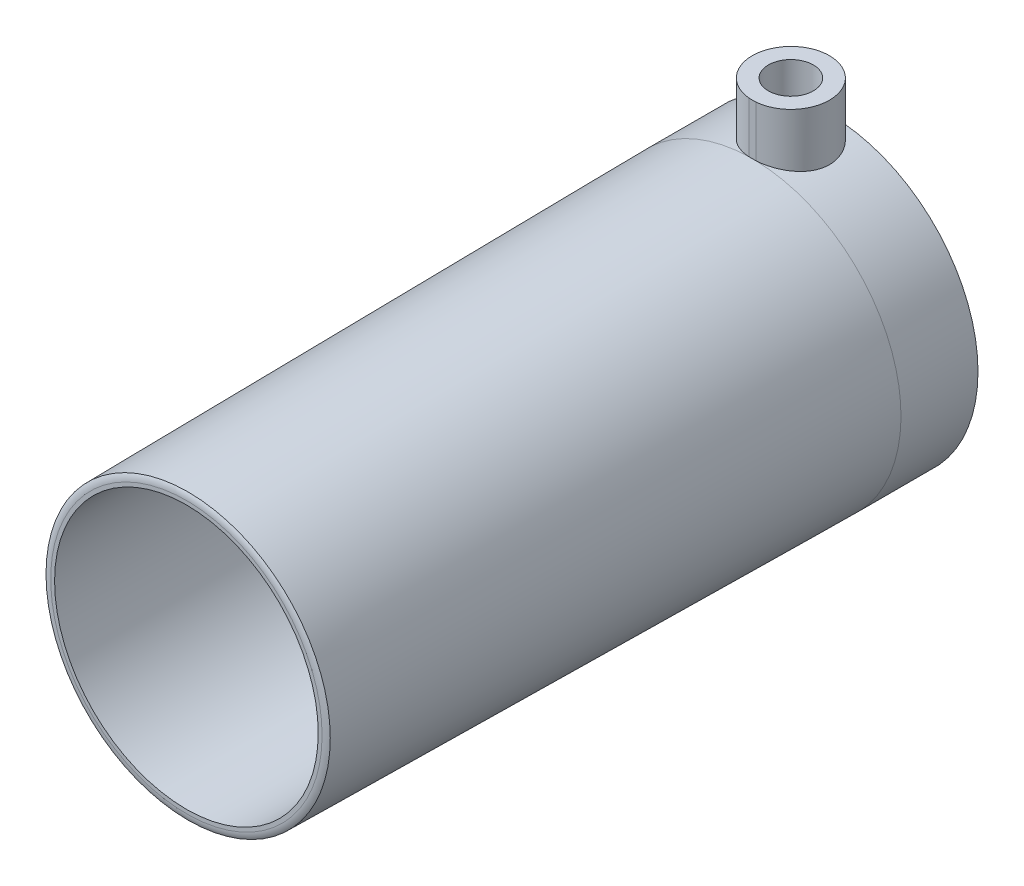
SolidWorks part; units mm, degrees
ref_plane "前视基准面" through (0, 0, 0) normal (0, 0, 1) x (1, 0, 0)
ref_plane "上视基准面" through (0, 0, 0) normal (0, 1, 0) x (1, 0, 0)
ref_plane "右视基准面" through (0, 0, 0) normal (1, 0, 0) x (0, 0, -1)
sketch "草图1" plane through (0, 0, 0) normal (0, 0, 1) x (1, 0, 0)
  circle A0 centre (0, 0) radius 23.1
  circle A1 centre (0, 0) radius 20.5
  dimension "D1" = 46.2
  dimension "D2" = 41
extrude "凸台-拉伸1" add sketch "草图1" along normal blind 100
ref_plane "基准面1" through (0, 21, 0) normal (0, 1, 0) x (1, 0, 0)
sketch "草图2" plane through (0, 21, 0) normal (0, 1, 0) x (1, 0, 0)
  line L0 (0, 0) -> (0, -100) construction
  line L1 (-23.1, -100) -> (23.1, -100) construction
  line L2 (-23.1, 0) -> (23.1, 0) construction
  circle A0 centre (0, -6) radius 6
  dimension "D1" = 12
extrude "凸台-拉伸2" add sketch "草图2" along normal blind 10
sketch "草图3" plane through (0, 31, 0) normal (0, 1, 0) x (1, 0, 0)
  circle A0 centre (0, -6) radius 3.5
  dimension "D1" = 7
extrude "切除-拉伸1" cut sketch "草图3" against normal blind 20
fillet "圆角1" radius 2 1 edges at (23.1, 0, 100)
sketch "草图4" plane through (0, 0, 0) normal (0, 1, 0) x (1, 0, 0)
  line L0 (0, -100) -> (0, 0) construction
  line L1 (-21.1, -100) -> (21.1, -100) construction
  line L3 (23.1, -98) -> (23.1, 0) construction
  line L4 (23.1, -11.9744) -> (22.1, -100)
  line L5 (22.1, -100) -> (36.7199, -100)
  line L6 (36.7199, -100) -> (36.7199, -11.9744)
  line L7 (36.7199, -11.9744) -> (23.1, -11.9744)
  point P5 (23.1, -11.9744)
  point P7 (23.1, -11.9744)
  dimension "D1" = 1
revolve "切除-旋转1" cut sketch "草图4" angle 360 about L0
